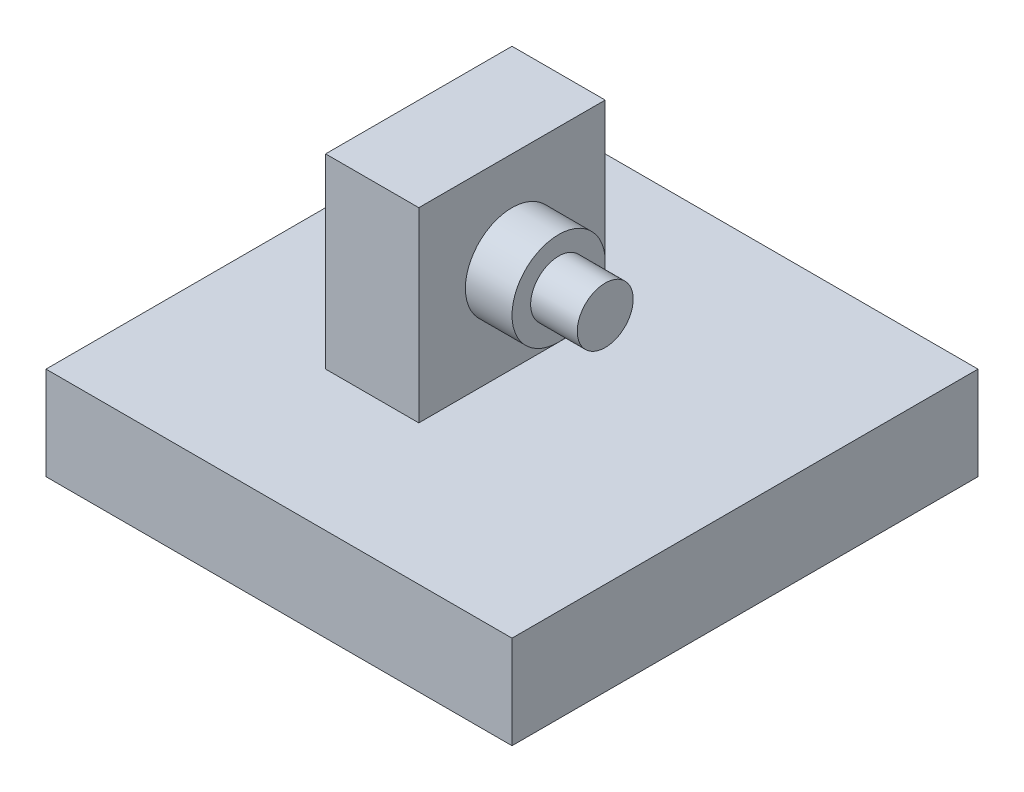
SolidWorks part; units mm, degrees
ref_plane "Ön Düzlem" through (0, 0, 0) normal (0, 0, 1) x (1, 0, 0)
ref_plane "Üst Düzlem" through (0, 0, 0) normal (0, 1, 0) x (1, 0, 0)
ref_plane "Sağ Düzlem" through (0, 0, 0) normal (1, 0, 0) x (0, 0, -1)
sketch "Çizim1" plane through (0, 0, 0) normal (0, 1, 0) x (1, 0, 0)
  line L1 (250, -250) -> (-250, -250)
  line L2 (250, -250) -> (250, 250)
  line L3 (250, 250) -> (-250, 250)
  line L4 (-250, -250) -> (-250, 250)
  point P0 (0, 0)
  dimension "D1" = 500
  dimension "D2" = 500
extrude "Yükseklik-Ekstrüzyon1" add sketch "Çizim1" along normal blind 100
sketch "Çizim2" plane through (0, 100, 0) normal (0, 1, 0) x (1, 0, 0)
  line L1 (0, -100) -> (-100, -100)
  line L2 (0, -100) -> (0, 100)
  line L3 (0, 100) -> (-100, 100)
  line L4 (-100, -100) -> (-100, 100)
  point P0 (0, 0)
  dimension "D1" = 200
  dimension "D2" = 100
extrude "Yükseklik-Ekstrüzyon2" add sketch "Çizim2" along normal blind 200
sketch "Çizim3" plane through (0, 0, 0) normal (1, 0, 0) x (0, 0, -1)
  circle A0 centre (0, 200) radius 50
  dimension "D1" = 100
extrude "Yükseklik-Ekstrüzyon3" add sketch "Çizim3" along normal blind 50
sketch "Çizim4" plane through (50, 0, 0) normal (1, 0, 0) x (0, 0, -1)
  circle A0 centre (0, 200) radius 30
  dimension "D1" = 60
extrude "Yükseklik-Ekstrüzyon4" add sketch "Çizim4" along normal blind 50
